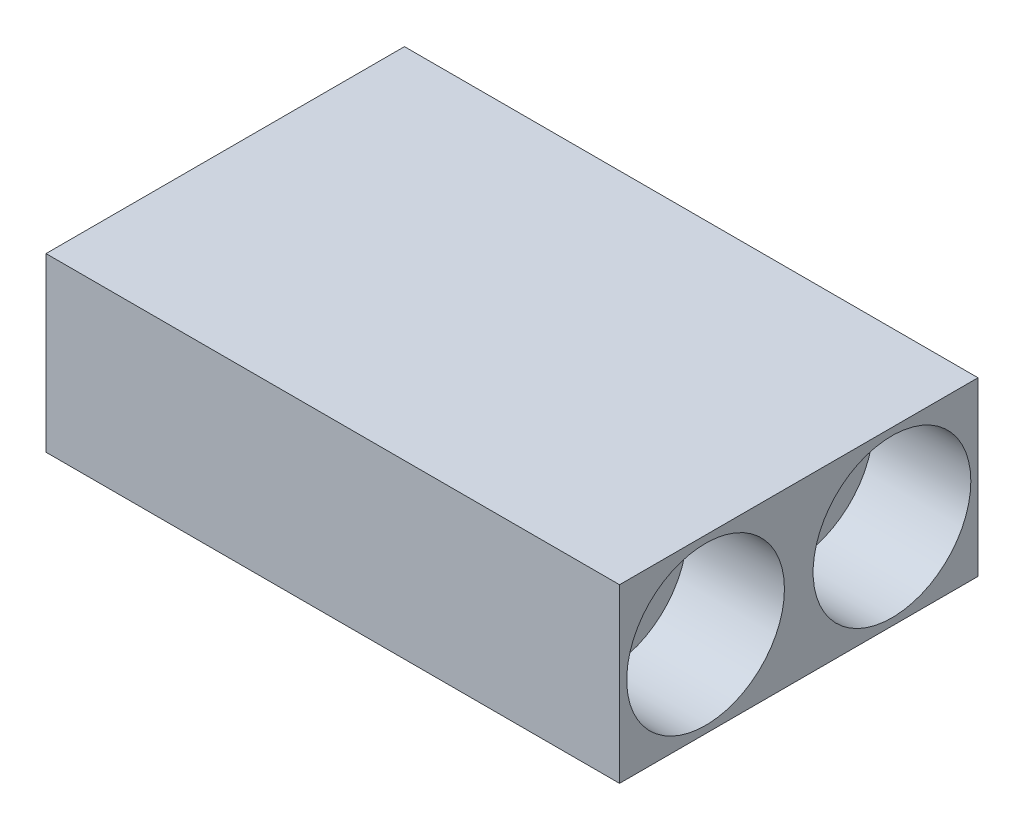
SolidWorks part; units mm, degrees
material "6061"
ref_plane "前视" through (0, 0, 0) normal (0, 0, 1) x (1, 0, 0)
ref_plane "上视" through (0, 0, 0) normal (0, 1, 0) x (1, 0, 0)
ref_plane "右视" through (0, 0, 0) normal (1, 0, 0) x (0, 0, -1)
sketch "草图1" plane through (0, 0, 0) normal (1, 0, 0) x (0, 0, -1)
  line L1 (-12.5, -6) -> (12.5, -6)
  line L2 (-12.5, -6) -> (-12.5, 6)
  line L3 (-12.5, 6) -> (12.5, 6)
  line L4 (12.5, -6) -> (12.5, 6)
  line L5 (-12.5, -6) -> (12.5, 6) construction
  line L6 (-12.5, 6) -> (12.5, -6) construction
  point P0 (0, 0)
  dimension "D1" = 12
  dimension "D2" = 25
extrude "凸台-拉伸1" add sketch "草图1" along normal blind 40
hole_wizard "打孔尺寸根据内六角圆柱头螺钉的类型1" positions "草图3" profile "草图2" counterbore size "M6" standard "Gb" end condition through all
sketch "草图3" plane through (40, 0, 0) normal (1, 0, 0) x (0, 0, -1)
  line L0 (0, 6) -> (0, 0) construction
  line L1 (12.5, 6) -> (-12.5, 6) construction
  line L2 (0, 0) -> (12.5, 0) construction
  line L3 (12.5, -6) -> (12.5, 6) construction
  point P0 (6.5, 0)
  point P14 (-6.5, 0)
  dimension "D1" = 13
sketch "草图2" plane through (40, 0, -6.5) normal (0, 1, 0) x (0, 0, -1)
  line L0 (0, 0) -> (0, 40)
  line L1 (0, 40) -> (3.3, 40)
  line L3 (3.3, 40) -> (3.3, 6.8)
  line L4 (3.3, 6.8) -> (5.5, 6.8)
  line L5 (5.5, 6.8) -> (5.5, 0)
  line L7 (5.5, 0) -> (0, 0)
  line L11 (0, -6.35) -> (0, 107.95) construction
  dimension "通孔孔直径" = 6.6
  dimension "通孔孔深度" = 40
  dimension "柱形沉头孔直径" = 11
  dimension "柱形沉头孔深度" = 6.8
